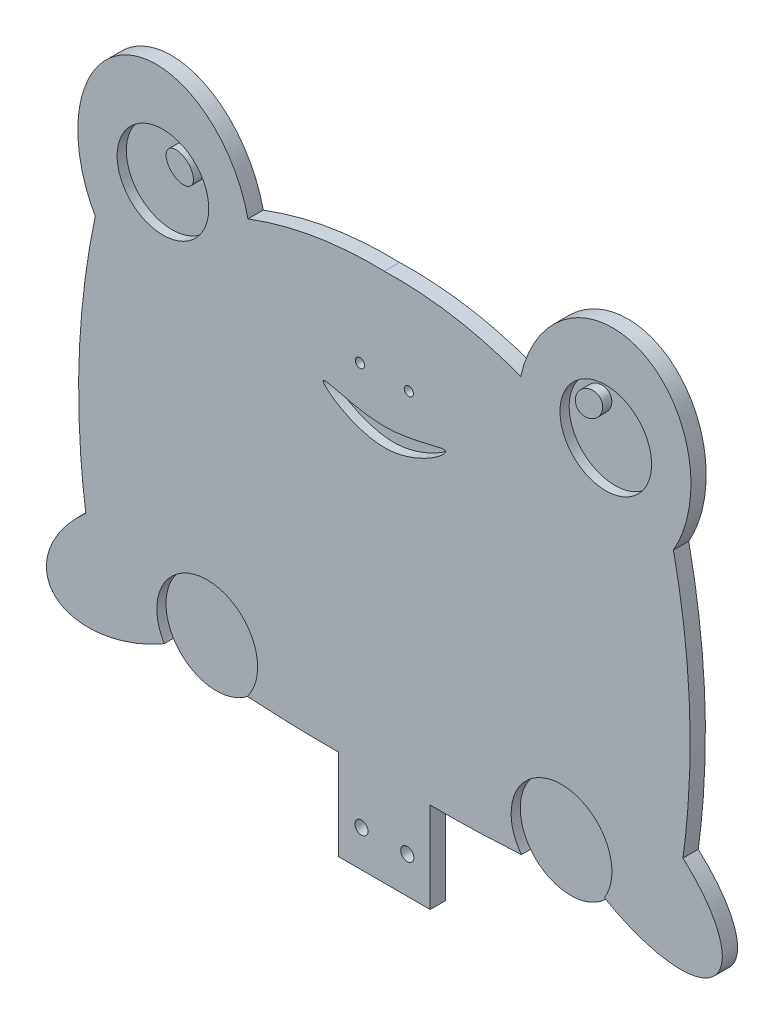
SolidWorks part; units mm, degrees
material "Acrylic (Medium-high impact)"
ref_plane "Front Plane" through (0, 0, 0) normal (0, 0, 1) x (1, 0, 0)
ref_plane "Top Plane" through (0, 0, 0) normal (0, 1, 0) x (1, 0, 0)
ref_plane "Right Plane" through (0, 0, 0) normal (1, 0, 0) x (0, 0, -1)
sketch "Sketch5" plane through (0, 0, 0) normal (0, 0, 1) x (1, 0, 0)
  line L0 (-45, -62.5) -> (-94.6601, 166.4747) construction
  line L1 (-100, 62.5) -> (100, 62.5) construction
  line L2 (-100, 62.5) -> (-100, -62.5) construction
  line L3 (-100, -62.5) -> (100, -62.5) construction
  line L4 (100, 62.5) -> (100, -62.5) construction
  line L5 (-100, 62.5) -> (100, -62.5) construction
  line L6 (-100, -62.5) -> (100, 62.5) construction
  line L7 (0, 115.2266) -> (0, -99.0086) construction
  line L9 (0, -55) -> (0, 55) construction
  line L10 (-15, -37.5) -> (15, -37.5)
  line L11 (-15, -37.5) -> (-15, -97.5)
  line L12 (-15, -97.5) -> (15, -97.5)
  line L13 (15, -37.5) -> (15, -97.5)
  line L14 (-15, -37.5) -> (15, -97.5) construction
  line L15 (-15, -97.5) -> (15, -37.5) construction
  circle A1 centre (-58, -57) radius 16.5
  circle A2 centre (58, -57) radius 16.5
  ellipse E0 centre (-72, 62.5) end of major axis (-64.4422, 28.1593) minor radius 28
  ellipse E1 centre (-79.5578, -49.7236) end of major axis (-49.8779, -31.1737) minor radius 17.5
  ellipse E2 centre (72, 62.5) end of major axis (64.4422, 28.1593) minor radius 28
  ellipse E3 centre (79.5578, -49.7236) end of major axis (109.2378, -68.2736) minor radius 17.5
  spline S0 degree 2 poles (-44.6544, 68.5183) (-23.0942, 76.659) (0, 76) knots 0 0 0 1 1 1
  spline S1 degree 2 poles (-94.6601, 44.2923) (-105.8893, -8.9635) (-94, -62.5) knots 0 0 0 1 1 1
  spline S2 degree 2 poles (-70.2829, -64.5636) (-35.2388, -68.9831) (0, -67.5) knots 0 0 0 1 1 1
  spline S3 degree 2 poles (44.6544, 68.5183) (23.0942, 76.659) (0, 76) knots 0 0 0 1 1 1
  spline S4 degree 2 poles (70.2829, -64.5636) (35.2388, -68.9831) (0, -67.5) knots 0 0 0 1 1 1
  spline S5 degree 2 poles (94.6601, 44.2923) (105.8893, -8.9635) (94, -62.5) knots 0 0 0 1 1 1
  point P0 (0, 0)
  dimension "D10" = 45.5689
  dimension "D14" = 35
  dimension "D12" = 107.6225
  dimension "D17" = 70.4267
  dimension "D19" = 33
  dimension "D1" = 200
  dimension "D2" = 125
  dimension "D3" = 28
  dimension "D4" = 12.237
  dimension "D5" = 55
  dimension "D6" = 56
  dimension "D7" = 68.6814
  dimension "D8" = 13.5
  dimension "D9" = 11.7
  dimension "D11" = 6
  dimension "D13" = 70
  dimension "D15" = 12.7764
  dimension "D16" = 5
  dimension "D18" = 5.2501
  dimension "D20" = 5.5
  dimension "D21" = 42
  dimension "D22" = 30
  dimension "D23" = 60
extrude "Boss-Extrude1" add sketch "Sketch5" along normal blind 5
sketch "Sketch6" plane through (0, 0, 5) normal (0, 0, 1) x (1, 0, 0)
  line L0 (-70.6864, 75.378) -> (-63.3136, 68.622) construction
  line L1 (-100, 75) -> (100, 75) construction
  line L2 (-100, 75) -> (-100, -75) construction
  line L3 (-100, -75) -> (100, -75) construction
  line L4 (100, 75) -> (100, -75) construction
  line L5 (-100, 75) -> (100, -75) construction
  line L6 (-100, -75) -> (100, 75) construction
  line L7 (0, -55) -> (0, 55) construction
  circle A0 centre (-72.5, 65) radius 15
  circle A1 centre (72.5, 65) radius 15
  ellipse E0 centre (-67, 72) end of major axis (-63.3136, 68.622) minor radius 3.75
  ellipse E1 centre (67, 72) end of major axis (63.3136, 68.622) minor radius 3.75
  point P2 (0, 0)
  dimension "D1" = 30
  dimension "D2" = 150
  dimension "D3" = 200
  dimension "D4" = 10
  dimension "D5" = 55
  dimension "D6" = 10
  dimension "D7" = 7.5
  dimension "D8" = 42.5
  dimension "D9" = 33
  dimension "D10" = 3
extrude "Cut-Extrude1" cut sketch "Sketch6" against normal blind 3 contours A0 | A1 | E1 | E0
sketch "Sketch8" plane through (0, 0, 5) normal (0, 0, 1) x (1, 0, 0)
  circle A0 centre (-8, 46) radius 1.5
  circle A1 centre (8, 46) radius 1.5
  spline S0 degree 3 poles (0, 18.3125) (-30.0438, 40.7762) (0, 27.7897) (30.0438, 40.7762) (0, 18.3125) (-30.0438, 40.7762) (0, 27.7897) knots -0.760129 -0.520258 -0.260129 0 0.239871 0.479742 0.739871 1 1.239871 1.479742 1.739871 only from (-20, 35) to (-20, 35)
  dimension "D9" = 3
  dimension "D11" = 3
  dimension "D1" = 32
  dimension "D2" = 26
  dimension "D3" = 40
  dimension "D4" = 35
  dimension "D5" = 20
  dimension "D6" = 6
  dimension "D7" = 20.2237
  dimension "D8" = 9
  dimension "D10" = 20
  dimension "D12" = 20
  dimension "D13" = 8
  dimension "D14" = 8
extrude "Cut-Extrude2" cut sketch "Sketch8" against normal blind 3
sketch "Sketch9" plane through (0, 0, 5) normal (0, 0, 1) x (1, 0, 0)
  line L0 (0, -55) -> (0, 55) construction
  circle A0 centre (-58, -57) radius 16.5
  arc A1 (-72.0587, -65.6372) -> (-44.8687, -66.9909) centre (-58, -57) ccw construction
  circle A2 centre (58, -57) radius 16.5
  dimension "D1" = 33
extrude "Cut-Extrude3" cut sketch "Sketch9" against normal blind 3
sketch "Sketch11" plane through (0, 0, 5) normal (0, 0, 1) x (1, 0, 0)
  line L0 (-15, -97.5) -> (15, -97.5) construction
  line L1 (-15, -67.864) -> (-15, -97.5) construction
  circle A0 centre (-7.5, -85.5) radius 2.15
  circle A1 centre (7.5, -85.5) radius 2.15
  dimension "D1" = 4.3
  dimension "D2" = 4.3
  dimension "D3" = 12
  dimension "D4" = 12
  dimension "D5" = 15
  dimension "D6" = 7.5
extrude "Cut-Extrude4" cut sketch "Sketch11" against normal through all
